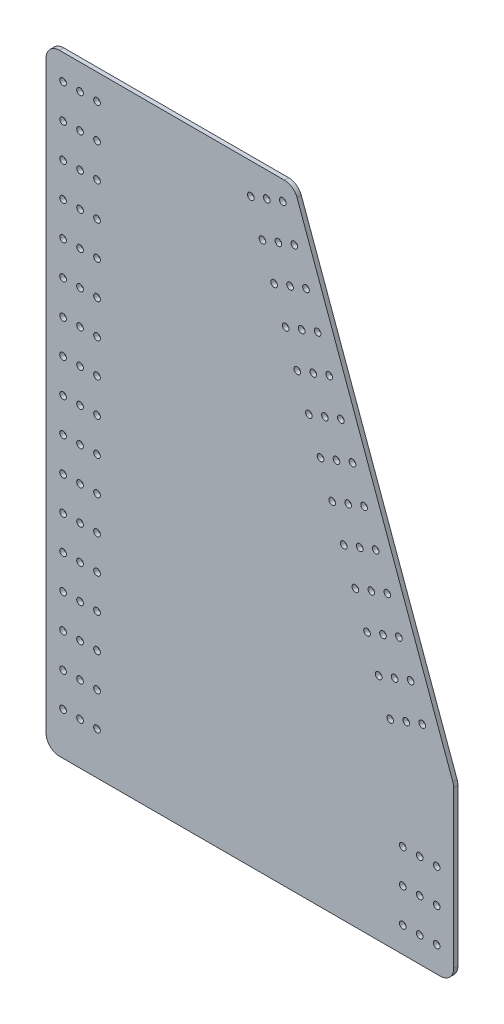
SolidWorks part; units mm, degrees
ref_plane "Front Plane" through (0, 0, 0) normal (0, 0, 1) x (1, 0, 0)
ref_plane "Top Plane" through (0, 0, 0) normal (0, 1, 0) x (1, 0, 0)
ref_plane "Right Plane" through (0, 0, 0) normal (1, 0, 0) x (0, 0, -1)
sketch "Sketch1" plane through (0, 0, 0) normal (0, 0, 1) x (1, 0, 0)
  line L1 (268.47, 228.6) -> (185.2664, 457.2)
  line L2 (185.2664, 457.2) -> (0, 457.2)
  line L3 (268.47, 228.6) -> (304.8, 128.7843)
  line L4 (304.8, 128.7843) -> (304.8, 0)
  line L6 (304.8, 0) -> (0, 0)
  line L7 (0, 0) -> (0, 457.2)
  point P2 (0, 0)
  dimension "D3" = 128.7843
  dimension "D24" = 106.2217
  dimension "D4" = 457.2
extrude "Boss-Extrude1" add sketch "Sketch1" along normal blind 3.175 contours L3 L4 L6 L7 L2 L1
fillet "Fillet1" radius 10 5 edges at (304.8, 0, 1.5875) (304.8, 128.7843, 1.5875) (0, 0, 1.5875) (185.2664, 457.2, 1.5875) (0, 457.2, 1.5875)
sketch "Sketch2" plane through (0, 0, 3.175) normal (0, 0, 1) x (1, 0, 0)
  line L0 (0, 10) -> (0, 447.2) construction
  line L1 (178.2644, 457.2) -> (10, 457.2) construction
  line L2 (304.8, 127.021) -> (304.8, 10) construction
  line L3 (294.8, 0) -> (10, 0) construction
  line L4 (12.7, 438.15) -> (12.7, 412.75) construction
  line L5 (153.1176, 434.1313) -> (165.0517, 438.475) construction
  line L6 (165.0517, 438.475) -> (176.9858, 442.8186) construction
  line L7 (304.1969, 130.4412) -> (187.6613, 450.6202) construction
  line L8 (266.7, 19.05) -> (266.7, 44.45) construction
  line L9 (153.1176, 434.1313) -> (161.8049, 410.2631) construction
  circle A0 centre (12.7, 438.15) radius 2.4892
  circle A1 centre (25.4, 438.15) radius 2.4892
  circle A2 centre (38.1, 438.15) radius 2.4892
  circle A3 centre (266.7, 19.05) radius 2.4892
  circle A4 centre (279.4, 19.05) radius 2.4892
  circle A5 centre (292.1, 19.05) radius 2.4892
  circle A6 centre (12.7, 412.75) radius 2.4892
  circle A7 centre (25.4, 412.75) radius 2.4892
  circle A8 centre (38.1, 412.75) radius 2.4892
  circle A9 centre (12.7, 387.35) radius 2.4892
  circle A10 centre (25.4, 387.35) radius 2.4892
  circle A11 centre (38.1, 387.35) radius 2.4892
  circle A12 centre (12.7, 361.95) radius 2.4892
  circle A13 centre (25.4, 361.95) radius 2.4892
  circle A14 centre (38.1, 361.95) radius 2.4892
  circle A15 centre (12.7, 336.55) radius 2.4892
  circle A16 centre (25.4, 336.55) radius 2.4892
  circle A17 centre (38.1, 336.55) radius 2.4892
  circle A18 centre (12.7, 311.15) radius 2.4892
  circle A19 centre (25.4, 311.15) radius 2.4892
  circle A20 centre (38.1, 311.15) radius 2.4892
  circle A21 centre (12.7, 285.75) radius 2.4892
  circle A22 centre (25.4, 285.75) radius 2.4892
  circle A23 centre (38.1, 285.75) radius 2.4892
  circle A24 centre (12.7, 260.35) radius 2.4892
  circle A25 centre (25.4, 260.35) radius 2.4892
  circle A26 centre (38.1, 260.35) radius 2.4892
  circle A27 centre (12.7, 234.95) radius 2.4892
  circle A28 centre (25.4, 234.95) radius 2.4892
  circle A29 centre (38.1, 234.95) radius 2.4892
  circle A30 centre (12.7, 209.55) radius 2.4892
  circle A31 centre (25.4, 209.55) radius 2.4892
  circle A32 centre (38.1, 209.55) radius 2.4892
  circle A33 centre (12.7, 184.15) radius 2.4892
  circle A34 centre (25.4, 184.15) radius 2.4892
  circle A35 centre (38.1, 184.15) radius 2.4892
  circle A36 centre (12.7, 158.75) radius 2.4892
  circle A37 centre (25.4, 158.75) radius 2.4892
  circle A38 centre (38.1, 158.75) radius 2.4892
  circle A39 centre (12.7, 133.35) radius 2.4892
  circle A40 centre (25.4, 133.35) radius 2.4892
  circle A41 centre (38.1, 133.35) radius 2.4892
  circle A42 centre (12.7, 107.95) radius 2.4892
  circle A43 centre (25.4, 107.95) radius 2.4892
  circle A44 centre (38.1, 107.95) radius 2.4892
  circle A45 centre (12.7, 82.55) radius 2.4892
  circle A46 centre (25.4, 82.55) radius 2.4892
  circle A47 centre (38.1, 82.55) radius 2.4892
  circle A48 centre (12.7, 57.15) radius 2.4892
  circle A49 centre (25.4, 57.15) radius 2.4892
  circle A50 centre (38.1, 57.15) radius 2.4892
  circle A51 centre (12.7, 31.75) radius 2.4892
  circle A52 centre (25.4, 31.75) radius 2.4892
  circle A53 centre (38.1, 31.75) radius 2.4892
  circle A57 centre (176.9858, 442.8186) radius 2.4892
  circle A58 centre (165.0517, 438.475) radius 2.4892
  circle A59 centre (153.1176, 434.1313) radius 2.4892
  circle A60 centre (266.7, 44.45) radius 2.4892
  circle A61 centre (279.4, 44.45) radius 2.4892
  circle A62 centre (292.1, 44.45) radius 2.4892
  circle A63 centre (266.7, 69.85) radius 2.4892
  circle A64 centre (279.4, 69.85) radius 2.4892
  circle A65 centre (292.1, 69.85) radius 2.4892
  circle A72 centre (161.8049, 410.2631) radius 2.4892
  circle A73 centre (173.739, 414.6068) radius 2.4892
  circle A74 centre (185.6731, 418.9504) radius 2.4892
  circle A75 centre (170.4922, 386.3949) radius 2.4892
  circle A76 centre (182.4263, 390.7386) radius 2.4892
  circle A77 centre (194.3604, 395.0822) radius 2.4892
  circle A78 centre (179.1795, 362.5267) radius 2.4892
  circle A79 centre (191.1136, 366.8704) radius 2.4892
  circle A80 centre (203.0477, 371.214) radius 2.4892
  circle A81 centre (187.8668, 338.6585) radius 2.4892
  circle A82 centre (199.8009, 343.0022) radius 2.4892
  circle A83 centre (211.735, 347.3459) radius 2.4892
  circle A84 centre (196.5541, 314.7903) radius 2.4892
  circle A85 centre (208.4882, 319.134) radius 2.4892
  circle A86 centre (220.4223, 323.4777) radius 2.4892
  circle A87 centre (205.2415, 290.9222) radius 2.4892
  circle A88 centre (217.1756, 295.2658) radius 2.4892
  circle A89 centre (229.1096, 299.6095) radius 2.4892
  circle A90 centre (213.9288, 267.054) radius 2.4892
  circle A91 centre (225.8629, 271.3976) radius 2.4892
  circle A92 centre (237.797, 275.7413) radius 2.4892
  circle A93 centre (222.6161, 243.1858) radius 2.4892
  circle A94 centre (234.5502, 247.5294) radius 2.4892
  circle A95 centre (246.4843, 251.8731) radius 2.4892
  circle A96 centre (231.3034, 219.3176) radius 2.4892
  circle A97 centre (243.2375, 223.6612) radius 2.4892
  circle A98 centre (255.1716, 228.0049) radius 2.4892
  circle A99 centre (239.9907, 195.4494) radius 2.4892
  circle A100 centre (251.9248, 199.793) radius 2.4892
  circle A101 centre (263.8589, 204.1367) radius 2.4892
  circle A102 centre (248.678, 171.5812) radius 2.4892
  circle A103 centre (260.6121, 175.9248) radius 2.4892
  circle A104 centre (272.5462, 180.2685) radius 2.4892
  circle A105 centre (257.3653, 147.713) radius 2.4892
  circle A106 centre (269.2994, 152.0567) radius 2.4892
  circle A107 centre (281.2335, 156.4003) radius 2.4892
  dimension "D1" = 4.9784
  dimension "D2" = 12.7
  dimension "D3" = 12.7
  dimension "D4" = 12.7
  dimension "D5" = 19.05
  dimension "D6" = 4.9784
  dimension "D7" = 12.7
  dimension "D8" = 12.7
  dimension "D9" = 12.7
  dimension "D10" = 19.05
  dimension "D13" = 12.7
  dimension "D14" = 12.7
  dimension "D15" = 12.7
  dimension "D16" = 4.9784
  dimension "D19" = 14.3814
  dimension "D12" = 25.4
  dimension "D18" = 25.4
  dimension "D21" = 25.4
  dimension "D11" = 17
  dimension "D17" = 3
  dimension "D20" = 13
extrude "Cut-Extrude1" cut sketch "Sketch2" against normal through all
sketch "Sketch3" plane through (0, 0, 0) normal (0, 0, -1) x (-1, 0, 0)
  line L0 (-1344.4273, 0) -> (48655.5727, 0) construction
  line L1 (-304.8, -1002.2603) -> (-304.8, 48997.7397) construction
  line L2 (-294.8, 0) -> (-10, 0) construction
  line L3 (-304.8, 127.021) -> (-304.8, 10) construction
  point P3 (-304.8, 0)
  point P5 (0, 0)
  point P6 (-363.195, -4.1721)
